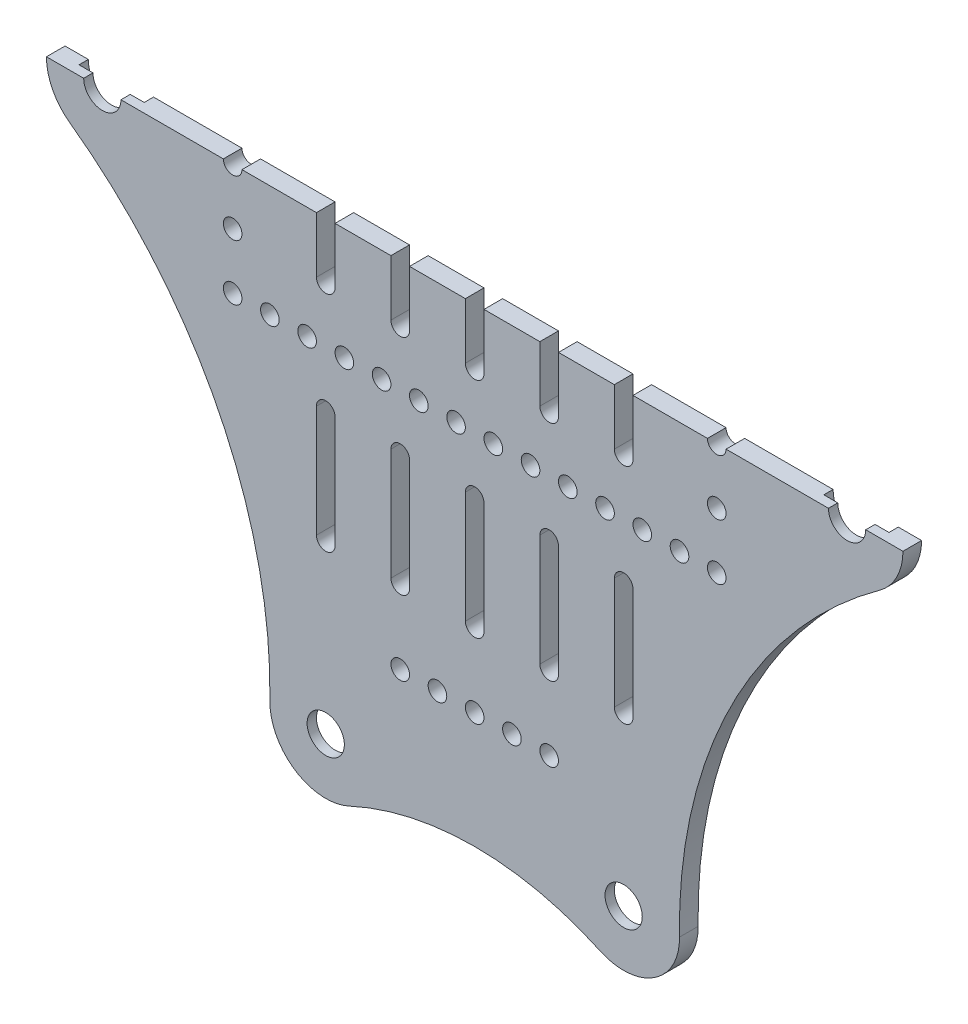
SolidWorks part; units mm, degrees
ref_plane "前视基准面" through (0, 0, 0) normal (0, 0, 1) x (1, 0, 0)
ref_plane "上视基准面" through (0, 0, 0) normal (0, 1, 0) x (1, 0, 0)
ref_plane "右视基准面" through (0, 0, 0) normal (1, 0, 0) x (0, 0, -1)
other "Configuration Table"
sketch "Sketch1" plane through (0, 0, 0) normal (0, 0, 1) x (1, 0, 0)
  line L0 (0, 0) -> (0, 120) construction
  line L1 (0, 120) -> (40, 120) construction
  line L2 (0, 0) -> (100, 0) construction
  circle A1 centre (100, 0) radius 15
  circle A2 centre (40, 120) radius 15
  circle A3 centre (-100, 0) radius 15
  circle A4 centre (-40, 120) radius 15
  circle A5 centre (40, -120) radius 15
  circle A6 centre (-40, -120) radius 15
  arc A7 (-33.6842, 133.6055) -> (33.6842, 133.6055) centre (0, 206.1684) ccw
  arc A8 (-33.6842, -133.6055) -> (33.6842, -133.6055) centre (0, -206.1684) cw
  arc A9 (-108.7909, 12.154) -> (-54.9978, 119.7403) centre (-184.9783, 117.4891) ccw
  arc A10 (108.7909, 12.154) -> (54.9978, 119.7403) centre (184.9783, 117.4891) cw
  arc A11 (108.7909, -12.154) -> (54.9978, -119.7403) centre (184.9783, -117.4891) ccw
  arc A12 (-108.7909, -12.154) -> (-54.9978, -119.7403) centre (-184.9783, -117.4891) cw
  dimension "D1" = 30
  dimension "D2" = 30
  dimension "D6" = 80
  dimension "D7" = 130
  dimension "D3" = 40
  dimension "D4" = 100
  dimension "D5" = 120
extrude "Boss-Extrude1" add sketch "Sketch1" along normal blind 5 contours A3 A12 A6 A8 A5 A11 A1 A10 A2 A7 A4 A9 | A3 | A4 | A2 | A1 | A5 | A6 A7
sketch "Sketch2" plane through (0, 0, 0) normal (0, 0, -1) x (-1, 0, 0)
  line L0 (0, 0) -> (0, 91.5521) construction
  line L1 (0, 0) -> (39.9574, 0) construction
  circle A0 centre (-40, 120) radius 5
  circle A1 centre (-100, 0) radius 5
  circle A2 centre (100, 0) radius 5
  circle A3 centre (40, 120) radius 5
  circle A4 centre (40, -120) radius 5
  circle A5 centre (-40, -120) radius 5
  dimension "D1" = 10
extrude "Cut-Extrude1" cut sketch "Sketch2" against normal through all
sketch "Sketch5" plane through (0, 0, 0) normal (0, 0, -1) x (-1, 0, 0)
  line L0 (0, 95) -> (0, 126.1684) construction
  line L1 (0, 95) -> (20, 95) construction
  line L2 (0, -95) -> (0, -126.1684) construction
  line L3 (0, 0) -> (50.0339, 0) construction
  line L5 (0, -95) -> (20, -95) construction
  circle A0 centre (20, 95) radius 2.5
  circle A1 centre (0, 95) radius 2.5
  circle A2 centre (10, 95) radius 2.5
  circle A17 centre (10, -95) radius 2.5
  circle A18 centre (0, -95) radius 2.5
  circle A19 centre (20, -95) radius 2.5
  arc A20 (-33.6842, 133.6055) -> (33.6842, 133.6055) centre (0, 206.1684) ccw construction
  circle A21 centre (-20, 95) radius 2.5
  circle A22 centre (-10, 95) radius 2.5
  arc A23 (33.6842, -133.6055) -> (-33.6842, -133.6055) centre (0, -206.1684) ccw construction
  circle A24 centre (-20, -95) radius 2.5
  circle A25 centre (-10, -95) radius 2.5
  dimension "D1" = 5
  dimension "D2" = 5
  dimension "D4" = 5
  dimension "D3" = 95
  dimension "D5" = 10
extrude "Cut-Extrude4" cut sketch "Sketch5" against normal blind 12.5
sketch "Sketch6" plane through (0, 0, 5) normal (0, 0, 1) x (1, 0, 0)
  line L110 (0, 0) -> (0, 75) construction
  line L111 (0, 75) -> (40, 75) construction
  line L112 (40, 75) -> (40, 45) construction
  line L113 (42.5, 75) -> (42.5, 45)
  line L114 (37.5, 75) -> (37.5, 45)
  line L115 (20, 75) -> (20, 45) construction
  line L116 (22.5, 75) -> (22.5, 45)
  line L117 (17.5, 75) -> (17.5, 45)
  line L118 (0, 75) -> (0, 45) construction
  line L119 (2.5, 75) -> (2.5, 45)
  line L120 (-2.5, 75) -> (-2.5, 45)
  line L121 (-20, 75) -> (-20, 45) construction
  line L122 (-17.5, 75) -> (-17.5, 45)
  line L123 (-22.5, 75) -> (-22.5, 45)
  line L124 (-40, 75) -> (-40, 45) construction
  line L125 (-37.5, 75) -> (-37.5, 45)
  line L126 (-42.5, 75) -> (-42.5, 45)
  line L127 (40, 120) -> (0, 120) construction
  line L128 (0, 15) -> (40, 15) construction
  line L129 (40, 15) -> (40, -15) construction
  line L130 (42.5, 15) -> (42.5, -15)
  line L131 (37.5, 15) -> (37.5, -15)
  line L132 (20, 15) -> (20, -15) construction
  line L133 (22.5, 15) -> (22.5, -15)
  line L134 (17.5, 15) -> (17.5, -15)
  line L135 (0, 15) -> (0, -15) construction
  line L136 (2.5, 15) -> (2.5, -15)
  line L137 (-2.5, 15) -> (-2.5, -15)
  line L138 (-20, 15) -> (-20, -15) construction
  line L139 (-17.5, 15) -> (-17.5, -15)
  line L140 (-22.5, 15) -> (-22.5, -15)
  line L141 (-40, 15) -> (-40, -15) construction
  line L142 (-37.5, 15) -> (-37.5, -15)
  line L143 (-42.5, 15) -> (-42.5, -15)
  line L144 (0, -45) -> (40, -45) construction
  line L145 (40, -45) -> (40, -75) construction
  line L146 (42.5, -45) -> (42.5, -75)
  line L147 (37.5, -45) -> (37.5, -75)
  line L148 (20, -45) -> (20, -75) construction
  line L149 (22.5, -45) -> (22.5, -75)
  line L150 (17.5, -45) -> (17.5, -75)
  line L151 (0, -45) -> (0, -75) construction
  line L152 (2.5, -45) -> (2.5, -75)
  line L153 (-2.5, -45) -> (-2.5, -75)
  line L154 (-20, -45) -> (-20, -75) construction
  line L155 (-17.5, -45) -> (-17.5, -75)
  line L156 (-22.5, -45) -> (-22.5, -75)
  line L157 (-40, -45) -> (-40, -75) construction
  line L158 (-37.5, -45) -> (-37.5, -75)
  line L159 (-42.5, -45) -> (-42.5, -75)
  arc A90 (42.5, 75) -> (37.5, 75) centre (40, 75) ccw
  arc A91 (37.5, 45) -> (42.5, 45) centre (40, 45) ccw
  arc A92 (22.5, 75) -> (17.5, 75) centre (20, 75) ccw
  arc A93 (17.5, 45) -> (22.5, 45) centre (20, 45) ccw
  arc A94 (2.5, 75) -> (-2.5, 75) centre (0, 75) ccw
  arc A95 (-2.5, 45) -> (2.5, 45) centre (0, 45) ccw
  arc A96 (-17.5, 75) -> (-22.5, 75) centre (-20, 75) ccw
  arc A97 (-22.5, 45) -> (-17.5, 45) centre (-20, 45) ccw
  arc A98 (-37.5, 75) -> (-42.5, 75) centre (-40, 75) ccw
  arc A99 (-42.5, 45) -> (-37.5, 45) centre (-40, 45) ccw
  arc A100 (42.5, 15) -> (37.5, 15) centre (40, 15) ccw
  arc A101 (37.5, -15) -> (42.5, -15) centre (40, -15) ccw
  arc A102 (22.5, 15) -> (17.5, 15) centre (20, 15) ccw
  arc A103 (17.5, -15) -> (22.5, -15) centre (20, -15) ccw
  arc A104 (2.5, 15) -> (-2.5, 15) centre (0, 15) ccw
  arc A105 (-2.5, -15) -> (2.5, -15) centre (0, -15) ccw
  arc A106 (-17.5, 15) -> (-22.5, 15) centre (-20, 15) ccw
  arc A107 (-22.5, -15) -> (-17.5, -15) centre (-20, -15) ccw
  arc A108 (-37.5, 15) -> (-42.5, 15) centre (-40, 15) ccw
  arc A109 (-42.5, -15) -> (-37.5, -15) centre (-40, -15) ccw
  arc A110 (42.5, -45) -> (37.5, -45) centre (40, -45) ccw
  arc A111 (37.5, -75) -> (42.5, -75) centre (40, -75) ccw
  arc A112 (22.5, -45) -> (17.5, -45) centre (20, -45) ccw
  arc A113 (17.5, -75) -> (22.5, -75) centre (20, -75) ccw
  arc A114 (2.5, -45) -> (-2.5, -45) centre (0, -45) ccw
  arc A115 (-2.5, -75) -> (2.5, -75) centre (0, -75) ccw
  arc A116 (-17.5, -45) -> (-22.5, -45) centre (-20, -45) ccw
  arc A117 (-22.5, -75) -> (-17.5, -75) centre (-20, -75) ccw
  arc A118 (-37.5, -45) -> (-42.5, -45) centre (-40, -45) ccw
  arc A119 (-42.5, -75) -> (-37.5, -75) centre (-40, -75) ccw
  point P115 (40, 60)
  point P123 (20, 60)
  point P130 (0, 60)
  point P137 (-20, 60)
  point P144 (-40, 60)
  point P153 (40, 0)
  point P160 (20, 0)
  point P167 (0, 0)
  point P174 (-20, 0)
  point P181 (-40, 0)
  point P189 (40, -60)
  point P196 (20, -60)
  point P203 (0, -60)
  point P210 (-20, -60)
  point P217 (-40, -60)
  dimension "D9" = 2.5
  dimension "D7" = 40
  dimension "D8" = 75
  dimension "D10" = 30
  dimension "D11" = 20
  dimension "D12" = 60
  dimension "D13" = 20
extrude "Cut-Extrude5" cut sketch "Sketch6" against normal blind 10
sketch "Sketch7" plane through (0, 0, 5) normal (0, 0, 1) x (1, 0, 0)
  line L4 (0, 0) -> (0, 30) construction
  line L5 (0, 30) -> (-65, 30) construction
  line L6 (0, 0) -> (85, 0) construction
  line L7 (0, -30) -> (-65, -30) construction
  circle A28 centre (-65, 30) radius 2.5
  circle A29 centre (-55, 30) radius 2.5
  circle A30 centre (-45, 30) radius 2.5
  circle A31 centre (-35, 30) radius 2.5
  circle A32 centre (-25, 30) radius 2.5
  circle A33 centre (-15, 30) radius 2.5
  circle A34 centre (-5, 30) radius 2.5
  circle A35 centre (5, 30) radius 2.5
  circle A36 centre (15, 30) radius 2.5
  circle A37 centre (25, 30) radius 2.5
  circle A38 centre (35, 30) radius 2.5
  circle A39 centre (45, 30) radius 2.5
  circle A40 centre (55, 30) radius 2.5
  circle A41 centre (65, 30) radius 2.5
  circle A42 centre (65, -30) radius 2.5
  circle A43 centre (55, -30) radius 2.5
  circle A44 centre (45, -30) radius 2.5
  circle A45 centre (35, -30) radius 2.5
  circle A46 centre (25, -30) radius 2.5
  circle A47 centre (15, -30) radius 2.5
  circle A48 centre (5, -30) radius 2.5
  circle A49 centre (-5, -30) radius 2.5
  circle A50 centre (-15, -30) radius 2.5
  circle A51 centre (-25, -30) radius 2.5
  circle A52 centre (-35, -30) radius 2.5
  circle A53 centre (-45, -30) radius 2.5
  circle A54 centre (-55, -30) radius 2.5
  circle A55 centre (-65, -30) radius 2.5
  dimension "D5" = 5
  dimension "D6" = 30
  dimension "D7" = 65
  dimension "D8" = 10
extrude "Cut-Extrude6" cut sketch "Sketch7" against normal blind 10
sketch "Sketch8" plane through (0, 0, 5) normal (0, 0, 1) x (1, 0, 0)
  line L5 (0, 0) -> (-65, 0) construction
  line L6 (-65, 0) -> (-40, 15) construction
  line L7 (-40, 15) -> (-65, 15) construction
  line L8 (-65, 15) -> (-65, 0) construction
  line L9 (0, 0) -> (0, 17.5) construction
  circle A6 centre (-65, 0) radius 2.5
  circle A7 centre (-65, 15) radius 2.5
  circle A8 centre (-65, -15) radius 2.5
  circle A9 centre (65, -15) radius 2.5
  circle A10 centre (65, 0) radius 2.5
  circle A11 centre (65, 15) radius 2.5
  dimension "D4" = 5
  dimension "D6" = 5
  dimension "D5" = 65
extrude "Cut-Extrude7" cut sketch "Sketch8" against normal blind 10
sketch "Sketch9" plane through (0, 0, 0) normal (0, 0, -1) x (-1, 0, 0)
  circle A1 centre (100, 0) radius 8.75
  circle A2 centre (40, 120) radius 8.75
  circle A3 centre (40, -120) radius 8.75
  circle A4 centre (-40, -120) radius 8.75
  circle A5 centre (-100, 0) radius 8.75
  circle A6 centre (-40, 120) radius 8.75
  dimension "D1" = 17.5
extrude "Cut-Extrude8" cut sketch "Sketch9" against normal blind 2.5
sketch "Sketch10" plane through (0, 0, 5) normal (0, 0, 1) x (1, 0, 0)
  line L0 (-115, 0) -> (115, 0)
  line L2 (-115, -135) -> (115, -135)
  line L3 (-115, -135) -> (-115, 135)
  line L4 (-115, 135) -> (115, 135)
  line L5 (115, -135) -> (115, 135)
  line L6 (-115, -135) -> (115, 135) construction
  line L7 (-115, 135) -> (115, -135) construction
  arc A0 (-108.7909, 12.154) -> (-108.7909, -12.154) centre (-100, 0) ccw construction
  arc A1 (108.7909, -12.154) -> (108.7909, 12.154) centre (100, 0) ccw construction
  point P8 (0, 0)
  dimension "D1" = 270
  dimension "D2" = 230
extrude "Cut-Extrude9" cut sketch "Sketch10" against normal blind 10 contours L0 L5 L4 L3
